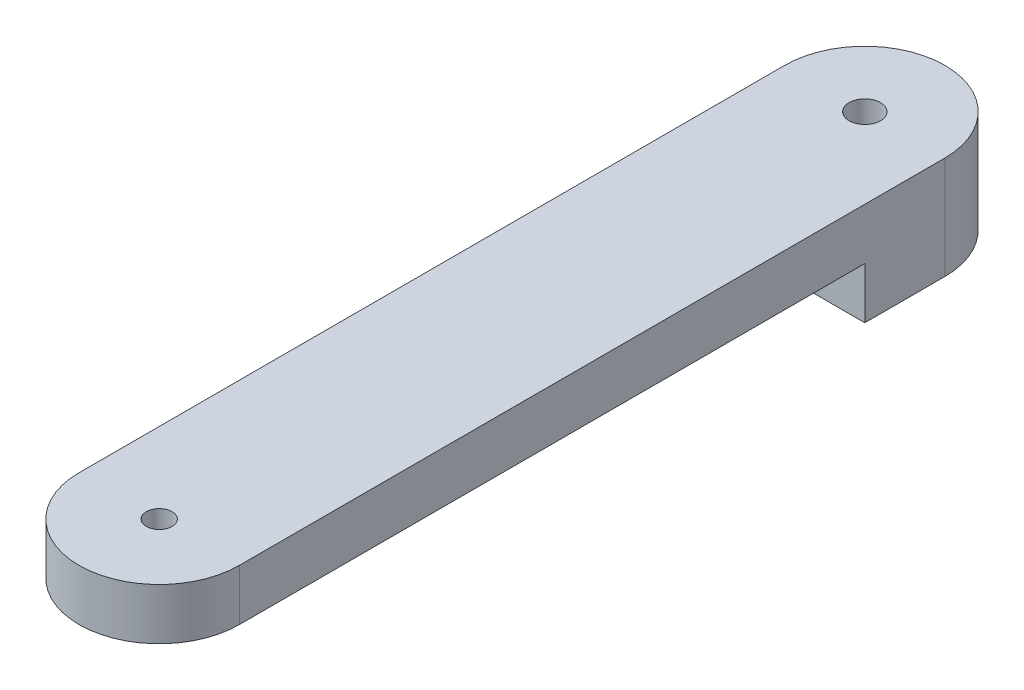
SolidWorks part; units mm, degrees
ref_plane "Front Plane" through (0, 0, 0) normal (0, 0, 1) x (1, 0, 0)
ref_plane "Top Plane" through (0, 0, 0) normal (0, 1, 0) x (1, 0, 0)
ref_plane "Right Plane" through (0, 0, 0) normal (1, 0, 0) x (0, 0, -1)
sketch "Sketch1" plane through (0, 0, 0) normal (0, 1, 0) x (1, 0, 0)
  line L0 (0, 0) -> (0, 110) construction
  line L1 (0, 55) -> (-25.4869, 55) construction
  line L2 (12.5, 110) -> (12.5, 0)
  line L3 (-12.5, 110) -> (-12.5, 0)
  circle A0 centre (0, 0) radius 5 construction
  circle A1 centre (0, 0) radius 12.5
  circle A2 centre (0, 110) radius 12.5
  circle A3 centre (0, 110) radius 2.45
  dimension "D2" = 4.9
  dimension "D3" = 10
  dimension "D4" = 25
  dimension "D1" = 110
  dimension "D5" = 25
extrude "Boss-Extrude1" add sketch "Sketch1" along normal blind 8 contours A2 L3 A1 L2 | A2 A3 | A1
sketch "Sketch2" plane through (0, 8, 0) normal (0, 1, 0) x (1, 0, 0)
  circle A0 centre (0, 0) radius 2
  dimension "D1" = 4
extrude "Cut-Extrude1" cut sketch "Sketch2" against normal through all both and the other way through all
sketch "Sketch3" plane through (0, 0, 0) normal (0, -1, 0) x (1, 0, 0)
  line L0 (12.5, -110) -> (12.5, 0) construction
  line L1 (-12.5, -110) -> (-12.5, 0) construction
  line L2 (12.5, -110) -> (12.5, -97.5)
  line L3 (-12.5, -110) -> (-12.5, -97.5)
  line L4 (-12.5, -97.5) -> (12.5, -97.5)
  arc A0 (-12.5, -110) -> (12.5, -110) centre (0, -110) ccw construction
  arc A1 (-12.5, -110) -> (12.5, -110) centre (0, -110) ccw
  point P7 (0, -122.5)
  dimension "D1" = 25
extrude "Boss-Extrude2" add sketch "Sketch3" along normal blind 8
sketch "Sketch4" plane through (0, 8, 0) normal (0, 1, 0) x (1, 0, 0)
  circle A0 centre (0, 110) radius 2.45 construction
  circle A1 centre (0, 110) radius 2.45
extrude "Cut-Extrude2" cut sketch "Sketch4" against normal through all both and the other way through all
